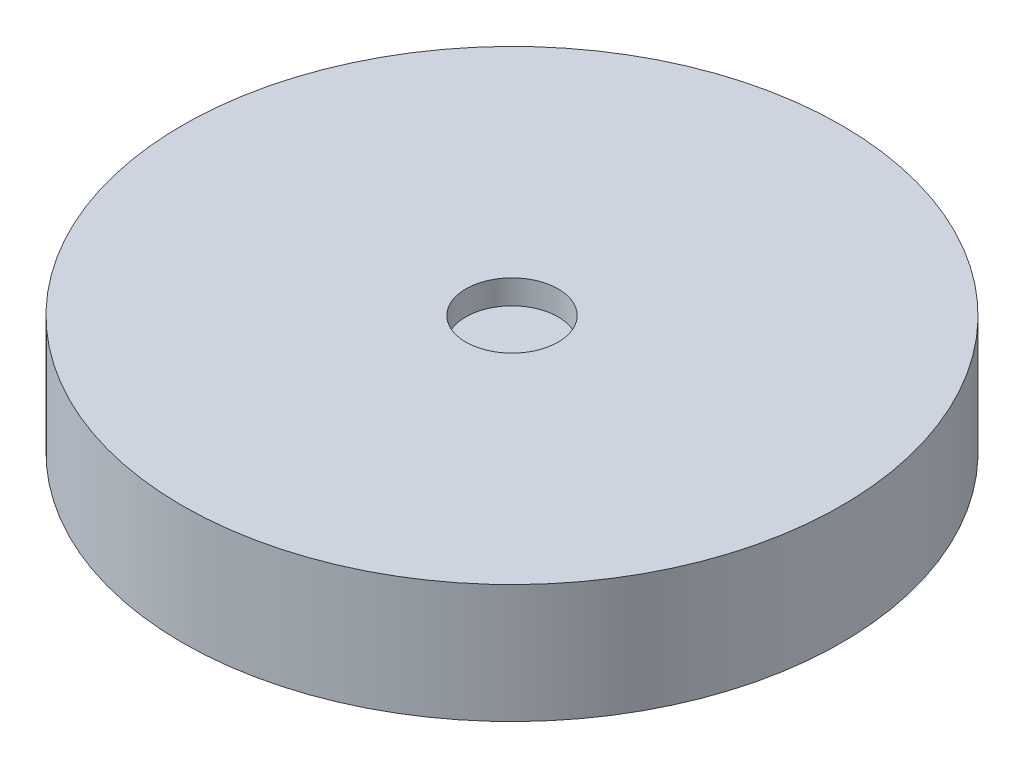
SolidWorks part; units mm, degrees
material "Balsa"
ref_plane "Alzado" through (0, 0, 0) normal (0, 0, 1) x (1, 0, 0)
ref_plane "Planta" through (0, 0, 0) normal (0, 1, 0) x (1, 0, 0)
ref_plane "Vista lateral" through (0, 0, 0) normal (1, 0, 0) x (0, 0, -1)
sketch "Croquis1" plane through (0, 0, 0) normal (0, 1, 0) x (1, 0, 0)
  circle A0 centre (0, 0) radius 25
  dimension "D1" = 50
extrude "Saliente-Extruir1" add sketch "Croquis1" along normal blind 9
sketch "Croquis2" plane through (0, 9, 0) normal (0, 1, 0) x (1, 0, 0)
  circle A0 centre (0, 0) radius 3.5
extrude "Cortar-Extruir1" cut sketch "Croquis2" against normal blind 1.8375
sketch "Croquis3" plane through (0, 0, 0) normal (0, -1, 0) x (1, 0, 0)
  circle A0 centre (0, 0) radius 25 construction
  point P0 (-4.0459, -24.6704)
